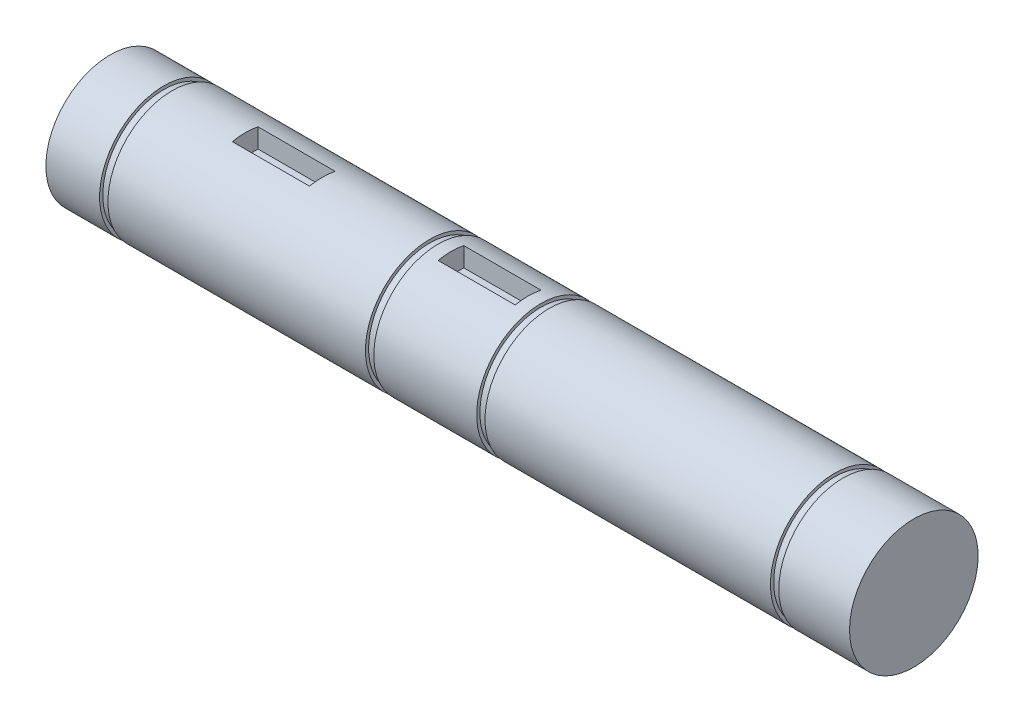
SolidWorks part; units mm, degrees
material "Alloy Steel"
ref_plane "Front Plane" through (0, 0, 0) normal (0, 0, 1) x (1, 0, 0)
ref_plane "Top Plane" through (0, 0, 0) normal (0, 1, 0) x (1, 0, 0)
ref_plane "Right Plane" through (0, 0, 0) normal (1, 0, 0) x (0, 0, -1)
sketch "Sketch1" plane through (0, 0, 0) normal (1, 0, 0) x (0, 0, -1)
  circle A0 centre (0, 0) radius 10
  dimension "D1" = 20
extrude "Boss-Extrude1" add sketch "Sketch1" along normal mid plane 155
ref_plane "Plane1" through (0, 10, 0) normal (0, 1, 0) x (1, 0, 0)
sketch "Sketch2" plane through (0, 10, 0) normal (0, 1, 0) x (1, 0, 0)
  line L0 (-77.5, 0) -> (-50.5, 0) construction
  line L1 (-77.5, 10) -> (-77.5, -10) construction
  line L2 (-50.5, 0) -> (-18.5, 0) construction
  line L3 (-18.5, 0) -> (66.5, 0) construction
  line L5 (-56.5, -2) -> (-44.5, -2)
  line L6 (-56.5, -2) -> (-56.5, 2)
  line L7 (-56.5, 2) -> (-44.5, 2)
  line L8 (-44.5, -2) -> (-44.5, 2)
  line L9 (-56.5, -2) -> (-44.5, 2) construction
  line L10 (-56.5, 2) -> (-44.5, -2) construction
  line L11 (-24.5, -2) -> (-12.5, -2)
  line L12 (-24.5, -2) -> (-24.5, 2)
  line L13 (-24.5, 2) -> (-12.5, 2)
  line L14 (-12.5, -2) -> (-12.5, 2)
  line L15 (-24.5, -2) -> (-12.5, 2) construction
  line L16 (-24.5, 2) -> (-12.5, -2) construction
  line L17 (60.5, -2) -> (72.5, -2)
  line L18 (60.5, -2) -> (60.5, 2)
  line L19 (60.5, 2) -> (72.5, 2)
  line L20 (72.5, -2) -> (72.5, 2)
  line L21 (60.5, -2) -> (72.5, 2) construction
  line L22 (60.5, 2) -> (72.5, -2) construction
  dimension "D1" = 12
  dimension "D2" = 4
  dimension "D3" = 27
  dimension "D4" = 32
  dimension "D5" = 85
extrude "Cut-Extrude1" cut sketch "Sketch2" against normal blind 3.2
sketch "Sketch4" plane through (0, 0, 0) normal (0, 0, 1) x (1, 0, 0)
  line L0 (-77.5, 10) -> (-77.5, -10) construction
  line L1 (-77.5, 10) -> (-77.5, -10) construction
  line L7 (-77.5, 0) -> (-77.3587, 0) construction
  line L8 (-56.8, 10) -> (-58.1, 10)
  line L9 (-18.5, 9.798) -> (-18.5, 14.8347) construction
  line L10 (-56.5, 10) -> (-77.5, 10) construction
  line L11 (-58.1, 10) -> (-58.1, 9.5)
  line L12 (-58.1, 9.5) -> (-56.8, 9.5)
  line L13 (-56.8, 9.5) -> (-56.8, 10)
  line L14 (-50.5, 9.798) -> (-50.5, 13.2481) construction
  line L15 (-44.5, 9.798) -> (-56.5, 9.798) construction
  line L16 (-44.2, 9.5) -> (-44.2, 10)
  line L17 (-44.2, 10) -> (-42.9, 10)
  line L18 (-42.9, 10) -> (-42.9, 9.5)
  line L19 (-42.9, 9.5) -> (-44.2, 9.5)
  line L20 (-27.8, 10) -> (-26.5, 10)
  line L21 (-24.5, 10) -> (-44.5, 10) construction
  line L22 (-26.5, 10) -> (-26.5, 9.5)
  line L23 (-26.5, 9.5) -> (-27.8, 9.5)
  line L24 (-27.8, 9.5) -> (-27.8, 10)
  line L25 (-12.5, 9.798) -> (-24.5, 9.798) construction
  line L26 (-10.5, 10) -> (-10.5, 9.5)
  line L27 (-10.5, 9.5) -> (-9.2, 9.5)
  line L28 (-9.2, 9.5) -> (-9.2, 10)
  line L29 (-9.2, 10) -> (-10.5, 10)
  line L30 (66.5, 9.798) -> (66.5, 15.9031) construction
  line L31 (72.5, 9.798) -> (60.5, 9.798) construction
  line L32 (58.5, 10) -> (58.5, 9.5)
  line L33 (60.5, 10) -> (-12.5, 10) construction
  line L34 (58.5, 9.5) -> (57.2, 9.5)
  line L35 (57.2, 9.5) -> (57.2, 10)
  line L36 (57.2, 10) -> (58.5, 10)
  line L37 (74.5, 10) -> (74.5, 9.5)
  line L38 (75.8, 10) -> (74.5, 10)
  line L39 (75.8, 9.5) -> (75.8, 10)
  line L40 (74.5, 9.5) -> (75.8, 9.5)
  line L41 (-5.25, 10) -> (-5.25, 9.5)
  line L42 (-5.25, 9.5) -> (-3.95, 9.5)
  line L43 (-3.95, 9.5) -> (-3.95, 10)
  line L44 (-3.95, 10) -> (-5.25, 10)
  line L45 (47.25, 10) -> (45.95, 10)
  line L46 (45.95, 10) -> (45.95, 9.5)
  line L47 (45.95, 9.5) -> (47.25, 9.5)
  line L48 (47.25, 9.5) -> (47.25, 10)
  line L49 (-29.9, 10) -> (-28.6, 10)
  line L50 (-28.6, 10) -> (-28.6, 9.5)
  line L51 (-28.6, 9.5) -> (-29.9, 9.5)
  line L52 (-29.9, 9.5) -> (-29.9, 10)
  line L53 (-75.4, 10) -> (-74.1, 10)
  line L54 (-74.1, 10) -> (-74.1, 9.5)
  line L55 (-74.1, 9.5) -> (-75.4, 9.5)
  line L56 (-75.4, 9.5) -> (-75.4, 10)
  dimension "D3" = 0.3
  dimension "D4" = 1.3
  dimension "D5" = 0.5
  dimension "D7" = 1.3
  dimension "D8" = 0.5
  dimension "D6" = 2
  dimension "D9" = 2
  dimension "D10" = 1.3
  dimension "D11" = 0.5
  dimension "D13" = 1.3
  dimension "D14" = 0.5
  dimension "D16" = 1.3
  dimension "D17" = 0.5
  dimension "D12" = 5.25
  dimension "D15" = 11.25
  dimension "D18" = 13
  dimension "D19" = 1.3
  dimension "D20" = 0.5
  dimension "D21" = 0.8
  dimension "D22" = 16
  dimension "D23" = 1.3
  dimension "D24" = 0.5
revolve "Cut-Revolve1" [suppressed] cut sketch "Sketch4" angle 360 about L7
sketch "Sketch5" plane through (0, 0, 0) normal (0, 0, 1) x (1, 0, 0)
  line L0 (-24.5, 10) -> (-44.5, 10) construction
  line L1 (-26.5, 10) -> (-27.8, 10)
  line L2 (-26.5, 10) -> (-26.5, 9.5)
  line L3 (-26.5, 9.5) -> (-27.8, 9.5)
  line L4 (-27.8, 10) -> (-27.8, 9.5)
  line L5 (-18.5, 9.798) -> (-18.5, 13.6364) construction
  line L6 (-12.5, 9.798) -> (-24.5, 9.798) construction
  line L7 (-10.5, 10) -> (-10.5, 9.5)
  line L8 (-10.5, 9.5) -> (-9.2, 9.5)
  line L9 (-9.2, 10) -> (-9.2, 9.5)
  line L10 (-10.5, 10) -> (-9.2, 10)
  line L11 (0, 0) -> (-40.9231, 0) construction
  line L12 (77.5, 10) -> (72.5, 10) construction
  line L13 (74.5, 10) -> (75.8, 10)
  line L14 (74.5, 10) -> (74.5, 9.5)
  line L15 (74.5, 9.5) -> (75.8, 9.5)
  line L16 (75.8, 10) -> (75.8, 9.5)
  line L17 (66.5, 9.798) -> (66.5, 12.8879) construction
  line L18 (72.5, 9.798) -> (60.5, 9.798) construction
  line L19 (57.2, 10) -> (57.2, 9.5)
  line L20 (58.5, 9.5) -> (57.2, 9.5)
  line L21 (58.5, 10) -> (58.5, 9.5)
  line L22 (58.5, 10) -> (57.2, 10)
  line L23 (77.5, 10) -> (47.5, 10) construction
  line L24 (60.5, 10) -> (-12.5, 10) construction
  line L25 (47.5, 10) -> (36.5, 10) construction
  line L26 (-77.5, 10) -> (-76.15, 10) construction
  line L27 (36.5, 10) -> (35.2, 10)
  line L28 (36.5, 10) -> (36.5, 9.5)
  line L29 (36.5, 9.5) -> (35.2, 9.5)
  line L30 (35.2, 10) -> (35.2, 9.5)
  line L31 (-56.5, 10) -> (-77.5, 10) construction
  line L32 (-76.15, 10) -> (-69.15, 10) construction
  line L34 (-69.15, 10) -> (-67.85, 10)
  line L35 (-69.15, 10) -> (-69.15, 9.5)
  line L36 (-69.15, 9.5) -> (-67.85, 9.5)
  line L37 (-67.85, 10) -> (-67.85, 9.5)
  dimension "D4" = 1.3
  dimension "D6" = 2
  dimension "D1" = 2
  dimension "D2" = 1.3
  dimension "D3" = 0.5
  dimension "D5" = 0.5
  dimension "D7" = 30
  dimension "D8" = 11
  dimension "D9" = 1.35
  dimension "D10" = 7
revolve "Cut-Revolve2" cut sketch "Sketch5" angle 360 about L11
sketch "Sketch6" plane through (0, 10, 0) normal (0, 1, 0) x (1, 0, 0)
  line L1 (77.5, 10) -> (47.5, 10)
  line L2 (77.5, 10) -> (77.5, -10)
  line L3 (77.5, -10) -> (47.5, -10)
  line L4 (47.5, 10) -> (47.5, -10)
  line L5 (36.5, -10) -> (57.2, -10) construction
  dimension "D1" = 30
extrude "Cut-Extrude2" cut sketch "Sketch6" against normal through all
equation "\"shaft-diameter\" =20mm"
equation "\"D1@Sketch1\"=\"shaft-diameter\""
equation "\"key-length\"=12mm"
equation "\"key-width\"=4mm"
equation "\"D1@Sketch2\"=\"key-length\""
equation "\"D2@Sketch2\"=\"key-width\""
equation "\"flippershaft-wormgear-diameter\" = 35mm"
equation "\"shaft-ring-groove-depth\"=0.5mm"
equation "\"shaft-ring-groove-width\" = 1.3mm"
equation "\"D5@Sketch4\"=\"shaft-ring-groove-depth\""
equation "\"D4@Sketch4\"=\"shaft-ring-groove-width\""
equation "\"D7@Sketch4\"=\"shaft-ring-groove-width\""
equation "\"D8@Sketch4\"=\"shaft-ring-groove-depth\""
equation "\"D10@Sketch4\"=\"shaft-ring-groove-width\""
equation "\"D11@Sketch4\"=\"shaft-ring-groove-depth\""
equation "\"D13@Sketch4\"=\"shaft-ring-groove-width\""
equation "\"D14@Sketch4\"=\"shaft-ring-groove-depth\""
equation "\"D16@Sketch4\"=\"shaft-ring-groove-width\""
equation "\"D17@Sketch4\"=\"shaft-ring-groove-depth\""
equation "\"D19@Sketch4\"=\"shaft-ring-groove-width\""
equation "\"D20@Sketch4\"=\"shaft-ring-groove-depth\""
equation "\"D23@Sketch4\"=\"shaft-ring-groove-width\""
equation "\"D24@Sketch4\"=\"shaft-ring-groove-depth\""
equation "\"D2@Sketch5\"=\"shaft-ring-groove-width\""
equation "\"D3@Sketch5\"=\"shaft-ring-groove-depth\""
equation "\"D4@Sketch5\"=\"shaft-ring-groove-width\""
equation "\"D5@Sketch5\"=\"shaft-ring-groove-depth\""
